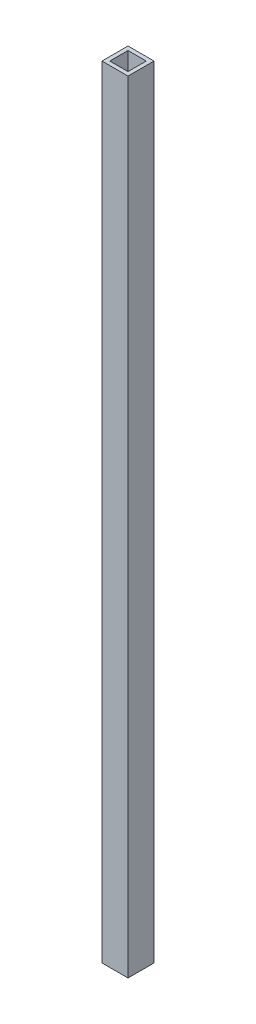
SolidWorks part; units mm, degrees
ref_plane "Front Plane" through (0, 0, 0) normal (0, 0, 1) x (1, 0, 0)
ref_plane "Top Plane" through (0, 0, 0) normal (0, 1, 0) x (1, 0, 0)
ref_plane "Right Plane" through (0, 0, 0) normal (1, 0, 0) x (0, 0, -1)
sketch "Sketch1" plane through (0, 0, 0) normal (0, 1, 0) x (1, 0, 0)
  line L0 (-3.5, 3.5) -> (3.5, 3.5)
  line L1 (-5, 5) -> (5, 5)
  line L2 (-5, 5) -> (-5, -5)
  line L3 (-5, -5) -> (5, -5)
  line L4 (5, 5) -> (5, -5)
  line L5 (-5, 5) -> (5, -5) construction
  line L6 (-5, -5) -> (5, 5) construction
  line L7 (3.5, 3.5) -> (3.5, -3.5)
  line L8 (-3.5, -3.5) -> (3.5, -3.5)
  line L9 (-3.5, 3.5) -> (-3.5, -3.5)
  point P0 (0, 0)
  dimension "D1" = 10
  dimension "D2" = 1.5
extrude "Boss-Extrude1" add sketch "Sketch1" along normal blind 300
